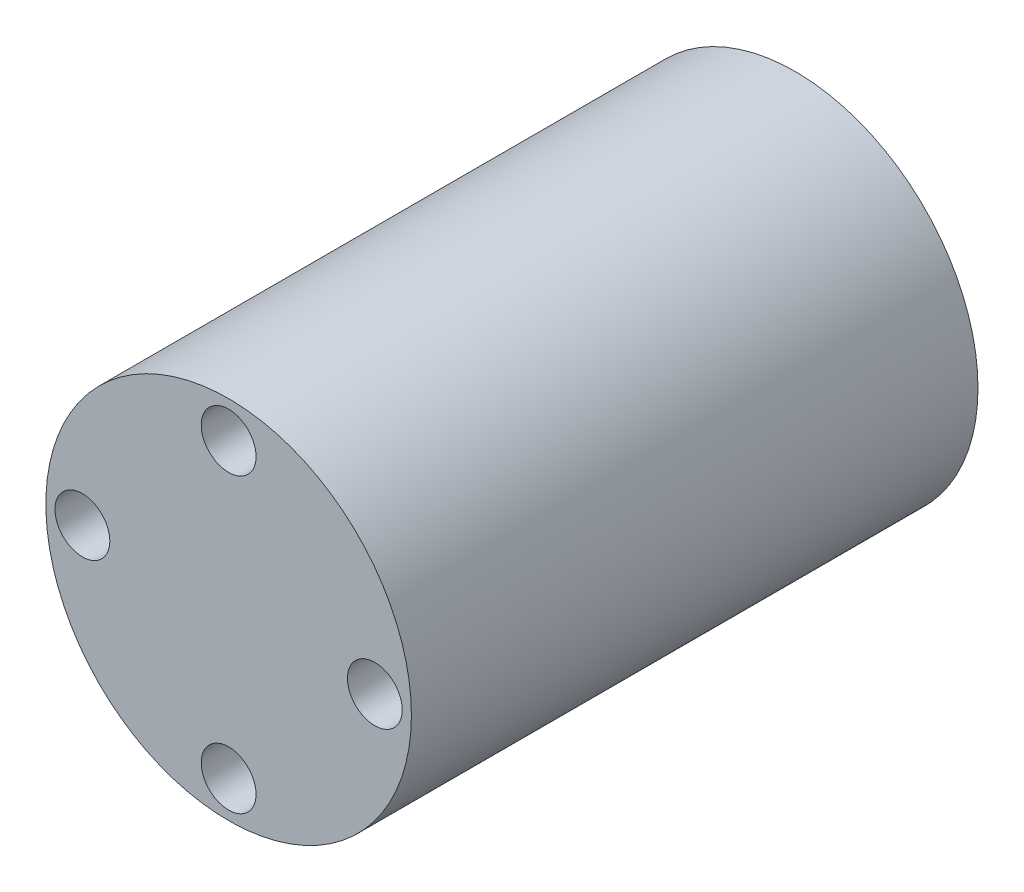
SolidWorks part; units mm, degrees
ref_plane "Ebene vorne" through (0, 0, 0) normal (0, 0, 1) x (1, 0, 0)
ref_plane "Ebene oben" through (0, 0, 0) normal (0, 1, 0) x (1, 0, 0)
ref_plane "Ebene rechts" through (0, 0, 0) normal (1, 0, 0) x (0, 0, -1)
sketch "Skizze1" plane through (0, 0, 0) normal (0, 0, 1) x (1, 0, 0)
  circle A0 centre (0, 0) radius 10
  circle A1 centre (0, 0) radius 8
  circle A2 centre (8, 0) radius 1.5
  circle A3 centre (0, 0) radius 9.5
  circle A4 centre (0, -8) radius 1.5
  circle A5 centre (-8, 0) radius 1.5
  circle A6 centre (0, 8) radius 1.5
  point P16 (0, 0)
  dimension "D1" = 20
  dimension "D2" = 19
  dimension "D3" = 3
  dimension "D4" = 4
extrude "Aufsatz-Linear austragen1" add sketch "Skizze1" along normal blind 31 contours A0 A3 | A6 A3 A5 A1 | A5 A3 A4 A1 | A4 A3 A2 A1 | A6 A1 A2 A3 | A6 A1 A5 A4 A2
